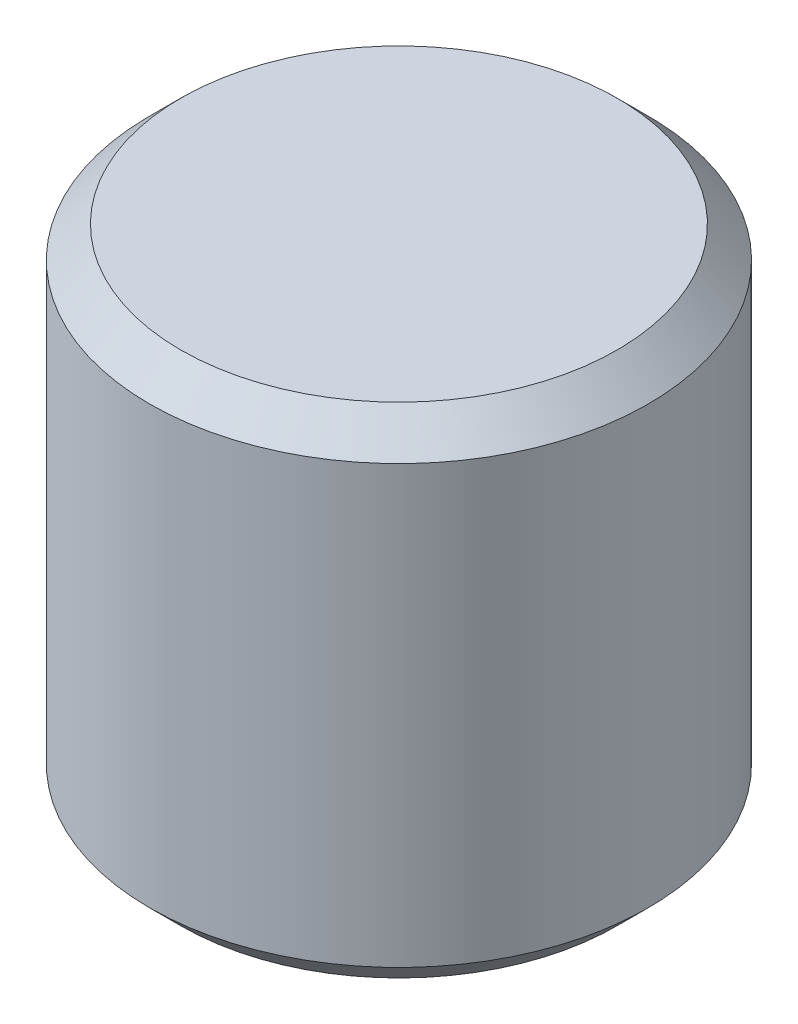
SolidWorks part; units mm, degrees
ref_plane "Front Plane" through (0, 0, 0) normal (0, 0, 1) x (1, 0, 0)
ref_plane "Top Plane" through (0, 0, 0) normal (0, 1, 0) x (1, 0, 0)
ref_plane "Right Plane" through (0, 0, 0) normal (1, 0, 0) x (0, 0, -1)
sketch "Sketch1" plane through (0, 0, 0) normal (0, 1, 0) x (1, 0, 0)
  circle A0 centre (0, 0) radius 2
  dimension "D1" = 4
extrude "Boss-Extrude1" add sketch "Sketch1" along normal blind 4
chamfer "Chamfer1" distance 0.25 angle 45 2 edges at (0, 0, 2) (0, 4, 2)
